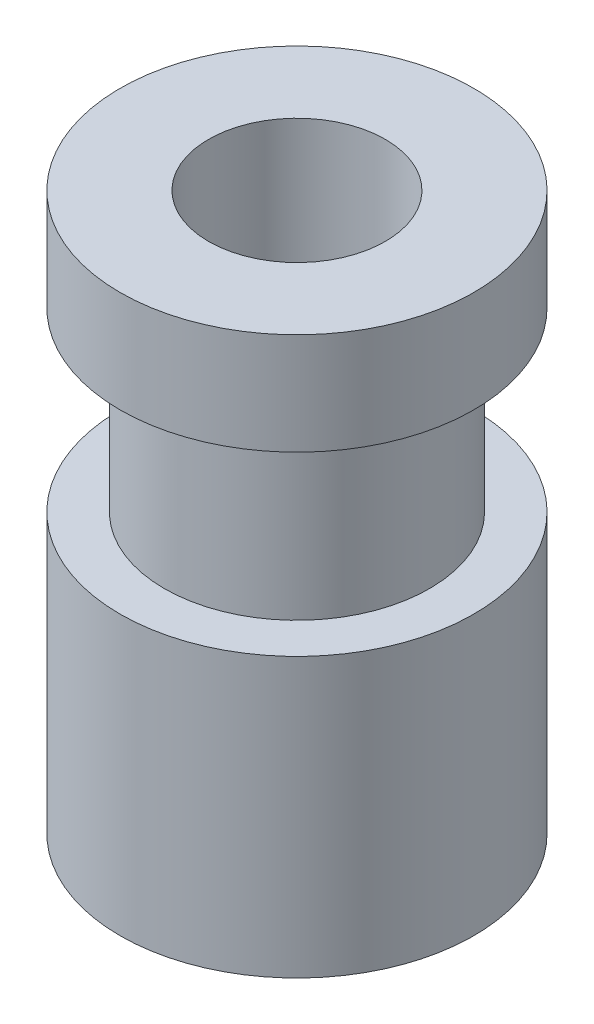
SolidWorks part; units mm, degrees
ref_plane "Plan de face" through (0, 0, 0) normal (0, 0, 1) x (1, 0, 0)
ref_plane "Plan de dessus" through (0, 0, 0) normal (0, 1, 0) x (1, 0, 0)
ref_plane "Plan de droite" through (0, 0, 0) normal (1, 0, 0) x (0, 0, -1)
sketch "Sketch1" plane through (0, 0, 0) normal (0, 1, 0) x (1, 0, 0)
  circle A0 centre (0, 0) radius 10
extrude "Boss-Extrude2" add sketch "Sketch1" along normal blind 10
sketch "Sketch5" plane through (0, 10, 0) normal (0, 1, 0) x (-1, 0, 0)
  circle A0 centre (0, 0) radius 1.5
extrude "Cut-Extrude3" cut sketch "Sketch5" against normal up to next
sketch "Sketch6" plane through (0, 10, 0) normal (0, 1, 0) x (-1, 0, 0)
  circle A0 centre (0, 0) radius 10
extrude "Boss-Extrude3" add sketch "Sketch6" along normal blind 5.75
sketch "Sketch7" plane through (0, 15.75, 0) normal (0, 1, 0) x (-1, 0, 0)
  circle A0 centre (0, 0) radius 5
extrude "Cut-Extrude4" cut sketch "Sketch7" against normal blind 5.75
sketch "Sketch8" plane through (0, 15.75, 0) normal (0, 1, 0) x (-1, 0, 0)
  circle A0 centre (0, 0) radius 7.5
extrude "Boss-Extrude4" add sketch "Sketch8" along normal blind 10
sketch "Sketch9" plane through (0, 25.75, 0) normal (0, 1, 0) x (-1, 0, 0)
  circle A0 centre (0, 0) radius 10
extrude "Boss-Extrude5" add sketch "Sketch9" along normal blind 5.75
sketch "Sketch10" plane through (0, 31.5, 0) normal (0, 1, 0) x (-1, 0, 0)
  circle A0 centre (0, 0) radius 5
extrude "Cut-Extrude5" cut sketch "Sketch10" against normal up to next
